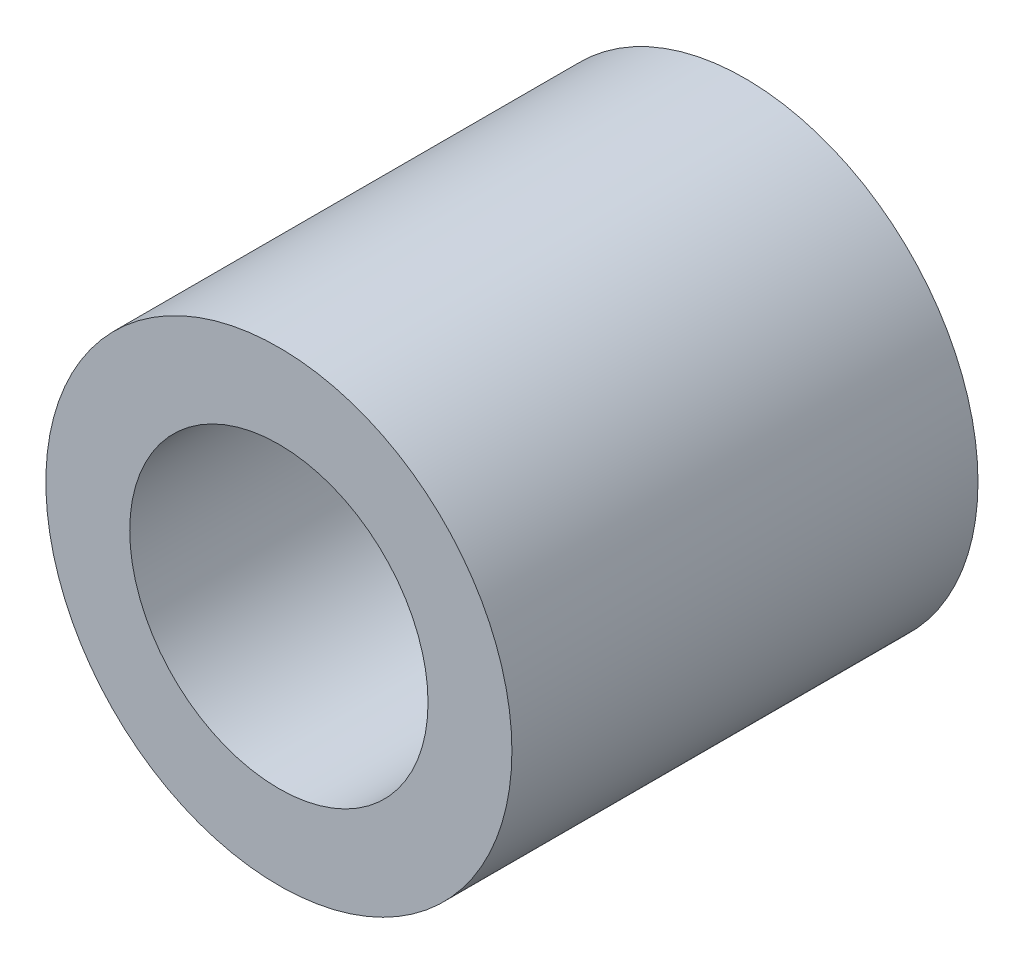
SolidWorks part; units mm, degrees
ref_plane "Front Plane" through (0, 0, 0) normal (0, 0, 1) x (1, 0, 0)
ref_plane "Top Plane" through (0, 0, 0) normal (0, 1, 0) x (1, 0, 0)
ref_plane "Right Plane" through (0, 0, 0) normal (1, 0, 0) x (0, 0, -1)
sketch "Sketch1" plane through (0, 0, 0) normal (0, 0, 1) x (1, 0, 0)
  circle A0 centre (0, 0) radius 1.6
  circle A1 centre (0, 0) radius 2.5
  dimension "D1" = 5
  dimension "D2" = 3.2
extrude "Boss-Extrude1" add sketch "Sketch1" along normal blind 5
